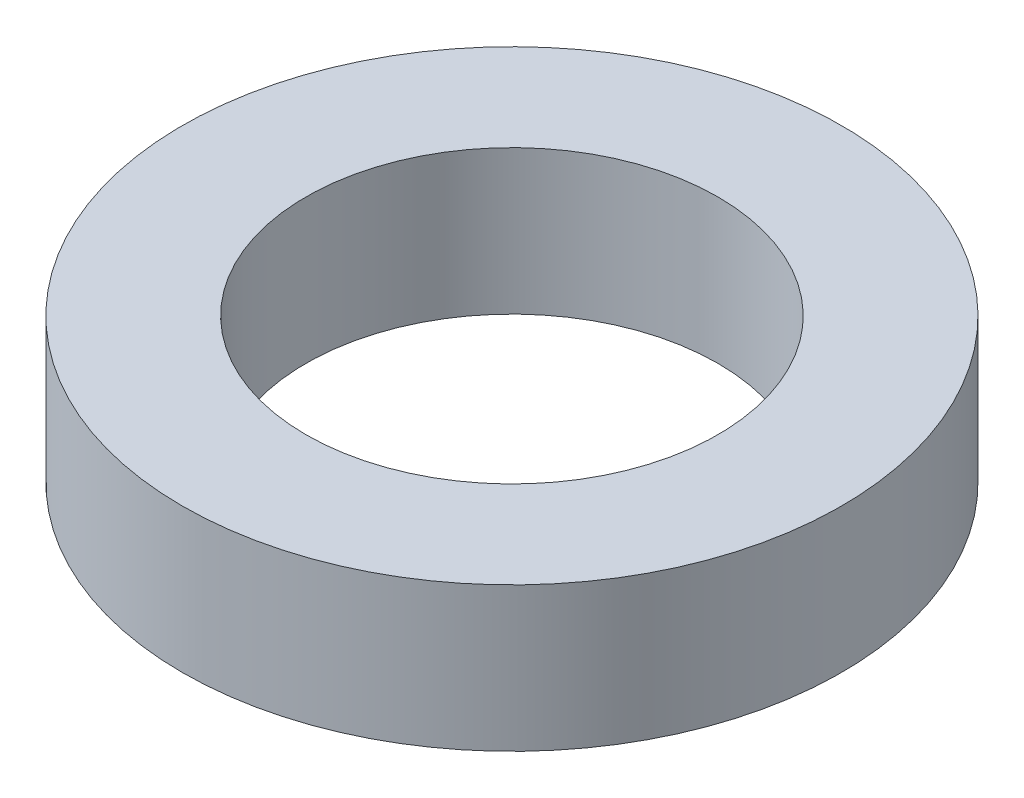
SolidWorks part; units mm, degrees
ref_plane "Спереди" through (0, 0, 0) normal (0, 0, 1) x (1, 0, 0)
ref_plane "Сверху" through (0, 0, 0) normal (0, 1, 0) x (1, 0, 0)
ref_plane "Справа" through (0, 0, 0) normal (1, 0, 0) x (0, 0, -1)
sketch "Эскиз1" plane through (0, 0, 0) normal (0, 1, 0) x (1, 0, 0)
  circle A0 centre (0, 0) radius 10
  circle A1 centre (0, 0) radius 16
  dimension "D1" = 20
  dimension "D2" = 32
extrude "Бобышка-Вытянуть1" add sketch "Эскиз1" along normal blind 7
